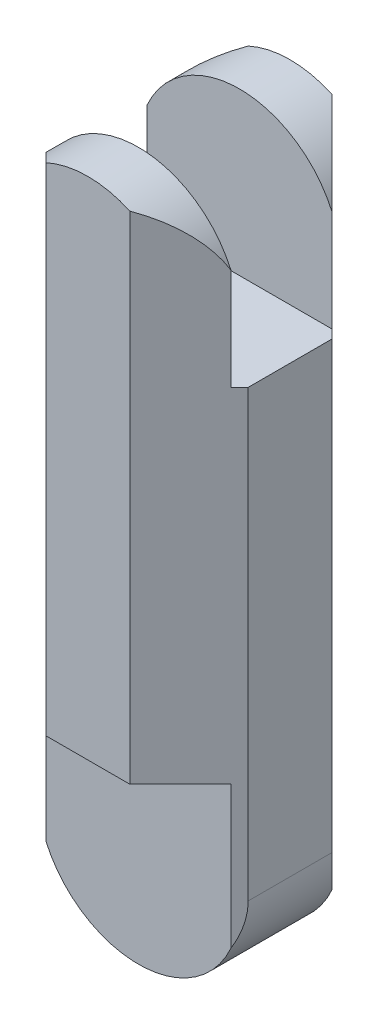
SolidWorks part; units mm, degrees
ref_plane "Front" through (0, 0, 0) normal (0, 0, 1) x (1, 0, 0)
ref_plane "Top" through (0, 0, 0) normal (0, 1, 0) x (1, 0, 0)
ref_plane "Right" through (0, 0, 0) normal (1, 0, 0) x (0, 0, -1)
sketch "草图1" plane through (0, 0, 0) normal (0, 1, 0) x (1, 0, 0)
  line L0 (-12.6518, 0) -> (13.462, 0) construction
  line L1 (0, 11.6722) -> (0, -14.1269) construction
  line L3 (10, 4.1421) -> (4.1421, 10)
  line L4 (4.1421, 10) -> (-4.1421, 10)
  line L5 (-4.1421, 10) -> (-10, 4.1421)
  line L6 (-10, 4.1421) -> (-10, -4.1421)
  line L7 (-10, -4.1421) -> (-4.1421, -10)
  line L8 (-4.1421, -10) -> (4.1421, -10)
  line L9 (4.1421, -10) -> (10, -4.1421)
  line L10 (10, -4.1421) -> (10, 4.1421)
  circle A0 centre (0, 0) radius 10 construction
extrude "凸台-拉伸1" add sketch "草图1" along normal blind 74
sketch "草图2" plane through (0, 0, 10) normal (0, 0, 1) x (1, 0, 0)
  line L0 (0, 0) -> (0, 24) construction
  line L7 (-10, 10) -> (-10, -2.3893)
  line L8 (-10, -2.3893) -> (10, -2.3893)
  line L9 (10, 10) -> (10, -2.3893)
  arc A1 (-10, 10) -> (10, 10) centre (0, 10) ccw
extrude "切除-拉伸1" cut sketch "草图2" against normal blind 66
sketch "草图4" plane through (0, 0, 10) normal (0, 0, 1) x (1, 0, 0)
  line L0 (10, 74) -> (10, 10) construction
  line L2 (-10, 10) -> (-10, 20)
  line L3 (-10, 20) -> (10, 20)
  line L4 (10, 10) -> (10, 20)
  arc A0 (-10, 10) -> (10, 10) centre (0, 10) ccw
extrude "切除-拉伸2" cut sketch "草图4" against normal blind 5
sketch "草图5" plane through (0, 0, -10) normal (0, 0, -1) x (-1, 0, 0)
  line L0 (10, 74) -> (10, 10) construction
  line L2 (-10, 10) -> (-10, 20)
  line L3 (-10, 20) -> (10, 20)
  line L4 (10, 10) -> (10, 20)
  arc A0 (-10, 10) -> (10, 10) centre (0, 10) ccw
extrude "切除-拉伸3" cut sketch "草图5" against normal blind 5
sketch "草图6" plane through (0, 0, 0) normal (0, 0, 1) x (1, 0, 0)
  line L0 (0, 74) -> (0, 0) construction
  line L1 (-4.1421, 74) -> (4.1421, 74) construction
  line L2 (10, 74) -> (10, 10) construction
  line L3 (-10, 74) -> (10, 74)
  line L4 (-10, 74) -> (-10, 54)
  line L5 (-10, 54) -> (10, 54)
  line L6 (10, 74) -> (10, 54)
  dimension "D1" = 20
extrude "切除-拉伸4" cut sketch "草图6" against normal mid plane 10
sketch "草图7" plane through (0, 0, 10) normal (0, 0, 1) x (1, 0, 0)
  line L0 (0, 74) -> (0, 0) construction
  line L1 (-4.1421, 74) -> (4.1421, 74) construction
  line L4 (-10, 60) -> (-10, 79.1079)
  line L5 (-10, 79.1079) -> (10, 79.1079)
  line L6 (10, 60) -> (10, 79.1079)
  arc A0 (10, 60) -> (-10, 60) centre (0, 60) ccw
extrude "切除-拉伸5" cut sketch "草图7" against normal blind 30
